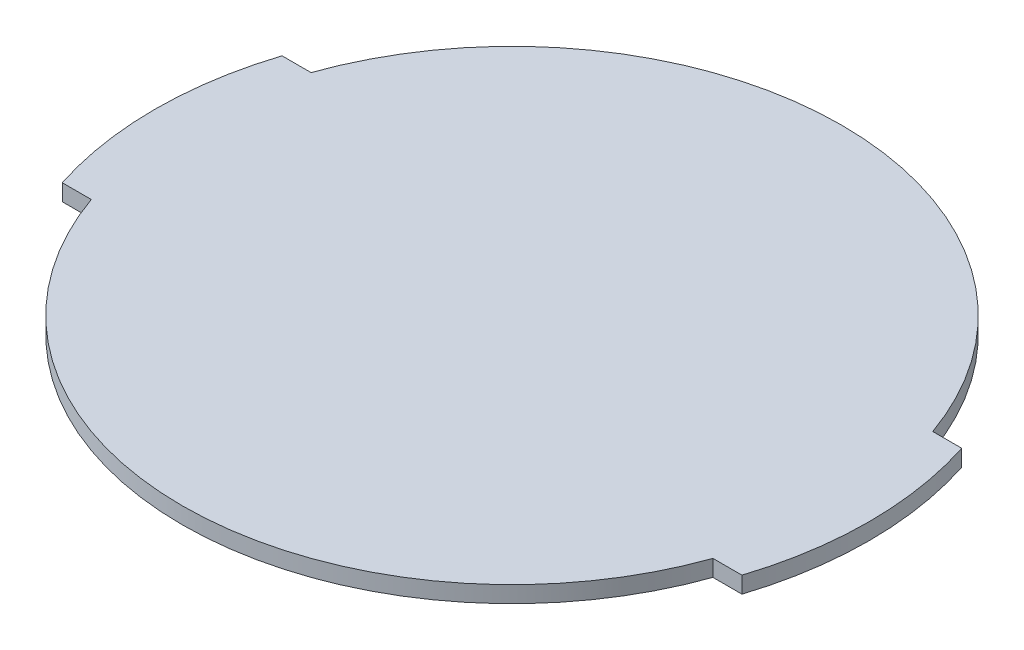
SolidWorks part; units mm, degrees
ref_plane "Front Plane" through (0, 0, 0) normal (0, 0, 1) x (1, 0, 0)
ref_plane "Top Plane" through (0, 0, 0) normal (0, 1, 0) x (1, 0, 0)
ref_plane "Right Plane" through (0, 0, 0) normal (1, 0, 0) x (0, 0, -1)
sketch "Sketch1" plane through (0, 0, 0) normal (0, 1, 0) x (1, 0, 0)
  line L0 (-61.8466, -20) -> (-56.5685, -20)
  line L1 (-61.8466, 20) -> (-56.5685, 20)
  line L2 (56.5685, 20) -> (61.8466, 20)
  line L3 (56.5685, -20) -> (61.8466, -20)
  line L4 (-32.8165, 0) -> (120.6229, 0) construction
  arc A0 (-56.5685, -20) -> (56.5685, -20) centre (0, 0) ccw
  arc A1 (-61.8466, 20) -> (-61.8466, -20) centre (0, 0) ccw
  arc A2 (61.8466, -20) -> (61.8466, 20) centre (0, 0) ccw
  arc A3 (56.5685, 20) -> (-56.5685, 20) centre (0, 0) ccw
  point P14 (120.6229, 0)
  dimension "D1" = 120
  dimension "D6" = 130
  dimension "D2" = 20
  dimension "D3" = 20
  dimension "D4" = 20
  dimension "D5" = 20
extrude "Boss-Extrude1" add sketch "Sketch1" along normal blind 3
